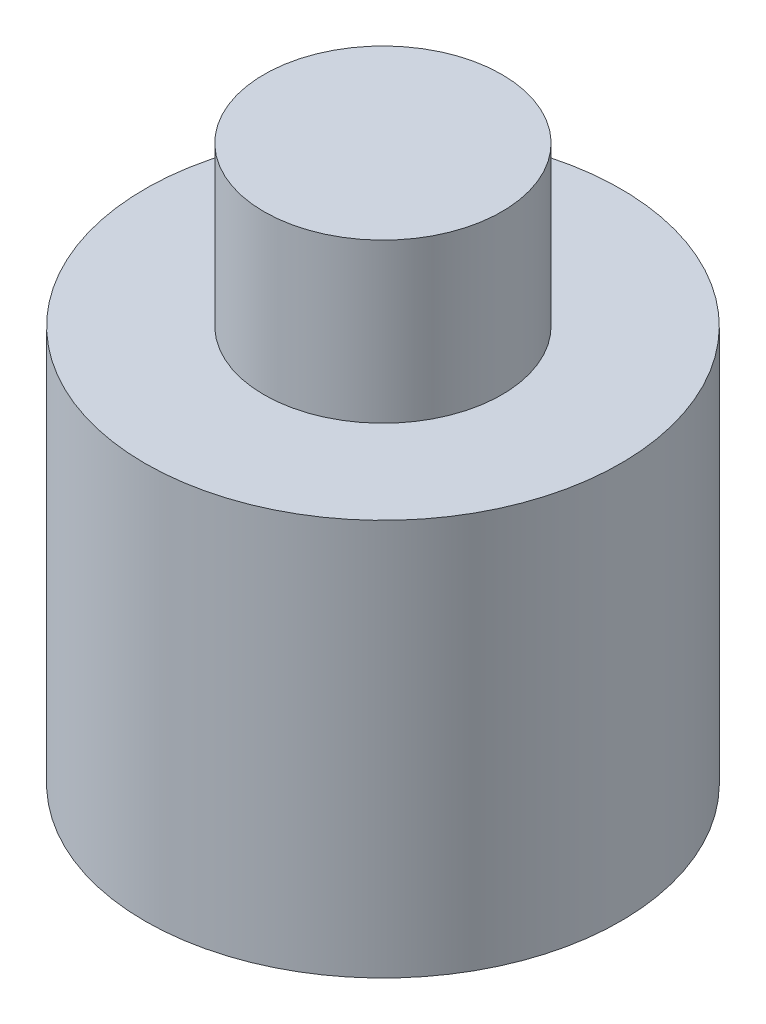
SolidWorks part; units mm, degrees
ref_plane "Front Plane" through (0, 0, 0) normal (0, 0, 1) x (1, 0, 0)
ref_plane "Top Plane" through (0, 0, 0) normal (0, 1, 0) x (1, 0, 0)
ref_plane "Right Plane" through (0, 0, 0) normal (1, 0, 0) x (0, 0, -1)
sketch "Sketch1" plane through (0, 0, 0) normal (0, 1, 0) x (1, 0, 0)
  circle A0 centre (0, 0) radius 30
  dimension "D1" = 60
extrude "Boss-Extrude1" add sketch "Sketch1" along normal blind 50
sketch "Sketch3" plane through (0, 50, 0) normal (0, 1, 0) x (1, 0, 0)
  circle A0 centre (0, 0) radius 15
  dimension "D1" = 30
extrude "Boss-Extrude3" add sketch "Sketch3" along normal blind 20
